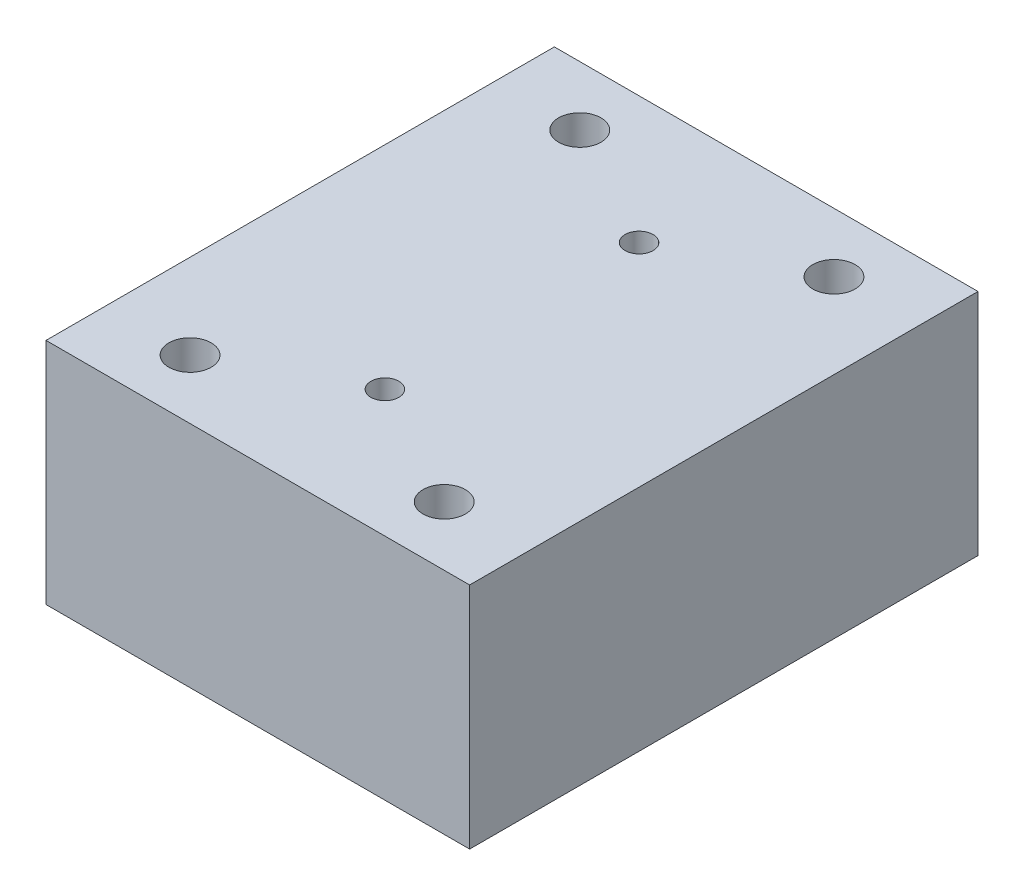
SolidWorks part; units mm, degrees
material "6061 Сплав"
ref_plane "Front" through (0, 0, 0) normal (0, 0, 1) x (1, 0, 0)
ref_plane "Top" through (0, 0, 0) normal (0, 1, 0) x (1, 0, 0)
ref_plane "Right" through (0, 0, 0) normal (1, 0, 0) x (0, 0, -1)
sketch "Эскиз1" plane through (0, 0, 0) normal (0, 0, 1) x (1, 0, 0)
  line L1 (-25, 13.5) -> (25, 13.5)
  line L2 (-25, 13.5) -> (-25, -13.5)
  line L3 (-25, -13.5) -> (25, -13.5)
  line L4 (25, 13.5) -> (25, -13.5)
  line L5 (-25, 13.5) -> (25, -13.5) construction
  line L6 (-25, -13.5) -> (25, 13.5) construction
  point P0 (0, 0)
  dimension "D1" = 27
  dimension "D2" = 50
extrude "Бобышка-Вытянуть1" add sketch "Эскиз1" along normal blind 60
sketch "Эскиз2" plane through (0, 13.5, 0) normal (0, 1, 0) x (1, 0, 0)
  line L0 (25, 0) -> (-25, 0) construction
  line L1 (-25, -60) -> (-25, 0) construction
  circle A0 centre (-15, -7) radius 2.5
  dimension "D1" = 7
  dimension "D2" = 10
extrude "Вырез-Вытянуть1" cut sketch "Эскиз2" against normal blind 27
pattern_linear "Линейный массив1" count 2 spacing 46 along (0, 0, 1) of "Вырез-Вытянуть1"
sketch "Эскиз3" plane through (0, 13.5, 0) normal (0, 1, 0) x (1, 0, 0)
  line L0 (25, -60) -> (25, 0) construction
  line L1 (25, 0) -> (-25, 0) construction
  circle A0 centre (15, -7) radius 2.5
  dimension "D1" = 10
  dimension "D2" = 7
extrude "Вырез-Вытянуть2" cut sketch "Эскиз3" against normal blind 27
pattern_linear "Линейный массив2" count 2 spacing 46 along (0, 0, 1) of "Вырез-Вытянуть2"
sketch "Эскиз4" plane through (0, 13.5, 0) normal (0, 1, 0) x (1, 0, 0)
  line L0 (25, -60) -> (25, 0) construction
  circle A0 centre (0, -15) radius 1.65
  circle A1 centre (0, -45) radius 1.65
  dimension "D1" = 30
  dimension "D2" = 15
  dimension "D3" = 25
  dimension "D4" = 25
extrude "Вырез-Вытянуть3" cut sketch "Эскиз4" against normal blind 27
